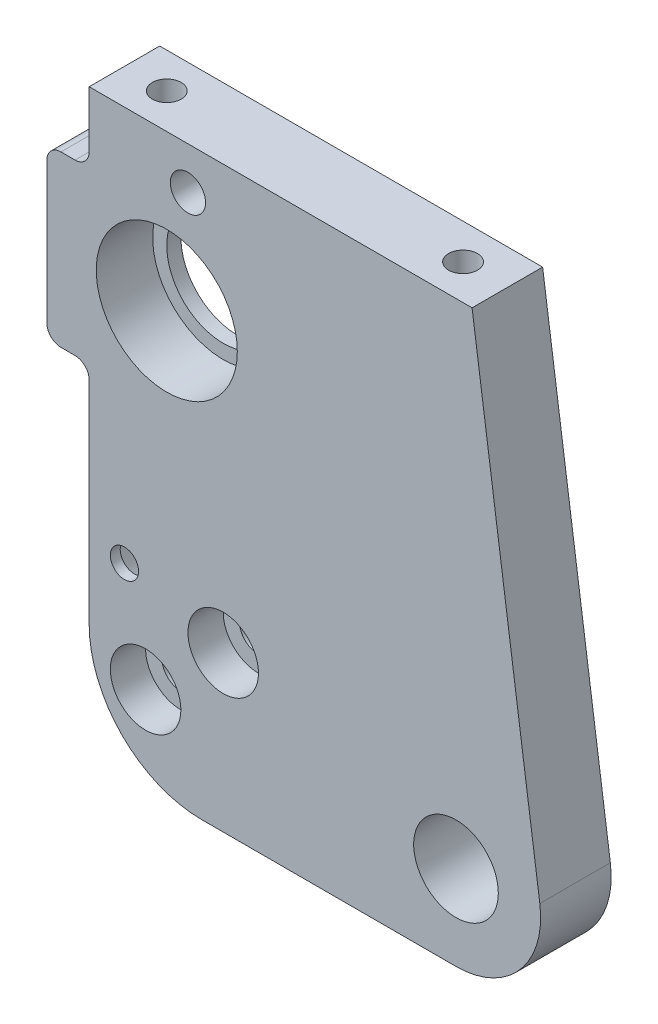
SolidWorks part; units mm, degrees
material "7075-O (SS)"
ref_plane "前视基准面" through (0, 0, 0) normal (0, 0, 1) x (1, 0, 0)
ref_plane "上视基准面" through (0, 0, 0) normal (0, 1, 0) x (1, 0, 0)
ref_plane "右视基准面" through (0, 0, 0) normal (1, 0, 0) x (0, 0, -1)
sketch "草图1" plane through (0, 0, 0) normal (0, 0, 1) x (1, 0, 0)
  line L1 (0, 0) -> (34, 0)
  line L2 (0, 0) -> (0, -41)
  line L3 (0, -41) -> (34, -41)
  line L4 (34, 0) -> (34, -41)
  dimension "D1" = 34
  dimension "D3" = 41
extrude "拉伸1" add sketch "草图1" along normal blind 5
fillet "圆角1" radius 8 1 edges at (0, -41, 2.5)
sketch "草图2" plane through (0, 0, 5) normal (0, 0, 1) x (1, 0, 0)
  line L0 (0, 0) -> (0, -33) construction
  line L2 (8, -41) -> (34, -41) construction
  circle A0 centre (26, -35) radius 3
  dimension "D2" = 6
  dimension "D3" = 6
  dimension "D1" = 26
extrude "拉伸2" cut sketch "草图2" against normal up to surface (5 mm away) up to face at (14.8686, -23.3314, 0)
sketch "草图3" plane through (0, 0, 5) normal (0, 0, 1) x (1, 0, 0)
  line L0 (0, 0) -> (0, -33) construction
  line L1 (0, -41) -> (34, -41) construction
  circle A0 centre (5.5, -11) radius 4
  dimension "D1" = 5.5
  dimension "D2" = 30
  dimension "D3" = 8
extrude "拉伸3" cut sketch "草图3" against normal up to surface (5 mm away) up to face at (29, -35, 0)
sketch "草图4" plane through (0, 0, 5) normal (0, 0, 1) x (1, 0, 0)
  circle A0 centre (5.5, -11) radius 5
  dimension "D1" = 10
extrude "拉伸4" cut sketch "草图4" against normal blind 4
sketch "草图5" plane through (0, 0, 0) normal (0, 1, 0) x (1, 0, 0)
  line L0 (3, -2.5) -> (24, -2.5)
  line L1 (34, 0) -> (0, 0) construction
  line L2 (17, 0) -> (17, -2.5) construction
  line L3 (0, -5) -> (0, 0) construction
  dimension "D1" = 2.5
  dimension "D2" = 21
  dimension "D3" = 3
hole_wizard "M2.5 螺纹孔1" positions "3D草图1" profile "草图6" tap size "M2.5" standard "GB"
sketch3d "3D草图1"
  point P0 (3, 0, 2.5)
  point P3 (24, 0, 2.5)
sketch "草图6" plane through (3, 0, 2.5) normal (1, 0, 0) x (0, 0, 1)
  line L0 (0, 0) -> (0, 7.9659)
  line L1 (0, 7.9659) -> (1.025, 7.35)
  line L2 (1.025, 7.35) -> (1.025, 0)
  line L5 (1.025, 0) -> (0, 0)
  line L10 (0, 7.9659) -> (-1.025, 7.35) construction
  line L11 (0, -6.35) -> (0, 107.95) construction
  dimension "螺纹孔钻头直径" = 2.05
  dimension "螺纹孔钻头深度" = 7.35
  dimension "导头角度" = 118
cosmetic thread "孔螺蚊线1" parameters "D1"=6, "D2"=2.5
cosmetic thread "孔螺蚊线2" parameters "D1"=6, "D2"=2.5
chamfer "倒角1" [suppressed] distance 0.5 angle 45
chamfer "倒角2" [suppressed] distance 0.5 angle 45
sketch "草图7" plane through (0, 0, 0) normal (0, 0, -1) x (-1, 0, 0)
  line L1 (-8, -41) -> (-34, -41) construction
  line L2 (-31.9416, -34.165) -> (-27.14, 0)
  line L3 (-34, 0) -> (0, 0) construction
  line L4 (-26, -41) -> (-34, -41)
  line L5 (-34, -41) -> (-34, 0) construction
  line L6 (-34, -41) -> (-34, 0)
  line L7 (-34, 0) -> (-27.14, 0)
  arc A0 (-31.9416, -34.165) -> (-26, -41) centre (-26, -35) ccw
  circle A1 centre (-26, -35) radius 3 construction
  dimension "D1" = 6
  dimension "D2" = 8
extrude "拉伸5" cut sketch "草图7" against normal up to surface (5 mm away) up to face at (10.5, -11, 5)
sketch "Sketch1" plane through (0, 0, 0) normal (0, 0, -1) x (-1, 0, 0)
  line L0 (-26, -41) -> (-12, -41)
  line L1 (0, 0) -> (0, -33) construction
  line L2 (0, -28.0198) -> (0, -29)
  line L3 (-29.4415, -39.9149) -> (0, -28.0198)
  line L4 (-26, -35) -> (-29.4415, -39.9149) construction
  line L5 (-8, -41) -> (-26, -41) construction
  arc A0 (-31.9416, -34.165) -> (-26, -41) centre (-26, -35) ccw construction
  arc A1 (-29.4415, -39.9149) -> (-26, -41) centre (-26, -35) ccw
  arc A3 (0, -29) -> (-12, -41) centre (-12, -29) cw
  dimension "D1" = 12
  dimension "D2" = 55
  dimension "D3" = 22
  dimension "D4" = 0
extrude "Extrude1" add sketch "Sketch1" against normal up to surface (5 mm away) up to face at (15.497, -25.3626, 5)
sketch "草图8" plane through (0, 0, 0) normal (0, 0, -1) x (-1, 0, 0)
  line L0 (-8, -41) -> (-26, -41) construction
  line L1 (0, 0) -> (0, -33) construction
  circle A0 centre (-2.5, -28) radius 1
  dimension "D3" = 2
  dimension "D1" = 13
  dimension "D2" = 2.5
extrude "拉伸6" cut sketch "草图8" against normal up to surface (5 mm away) up to face at (15.497, -25.3626, 5)
sketch "草图9" plane through (0, 0, 0) normal (0, 0, -1) x (-1, 0, 0)
  line L0 (-0.7612, -30.7586) -> (-4.7079, -32.1951)
  line L1 (-0.1635, -29.4769) -> (-2.626, -22.7111)
  line L2 (-5.9896, -31.5974) -> (-8.4521, -24.8316)
  line L3 (-3.9078, -22.1134) -> (-7.8545, -23.5499)
  line L4 (-2.5, -28) -> (-7.596, -28) construction
  line L5 (-2.5, -28) -> (-2.5, -23.308) construction
  line L6 (-4, -20.9273) -> (-4, -31.0273) construction
  line L7 (0, 0) -> (0, -33) construction
  line L8 (-4, -28) -> (-5.8811, -22.8317) construction
  arc A0 (-0.1635, -29.4769) -> (-0.7612, -30.7586) centre (-1.1032, -29.8189) cw
  arc A1 (-3.9078, -22.1134) -> (-2.626, -22.7111) centre (-3.5657, -23.0531) cw
  arc A2 (-8.4521, -24.8316) -> (-7.8545, -23.5499) centre (-7.5124, -24.4896) cw
  arc A3 (-4.7079, -32.1951) -> (-5.9896, -31.5974) centre (-5.0499, -31.2554) cw
  point P10 (-4, -28)
  point P19 (-2.9681, -21.7714)
  point P22 (-8.7942, -23.892)
  point P25 (-5.6476, -32.5371)
  dimension "D6" = 1
  dimension "D1" = 1.5
  dimension "D2" = 5.5
  dimension "D3" = 9.2
  dimension "D4" = 6.2
  dimension "D5" = 20
extrude "拉伸7" cut sketch "草图9" against normal blind 2.5
sketch "草图10" plane through (0, 0, 2.5) normal (0, 0, -1) x (-1, 0, 0)
  circle A0 centre (-4, -28) radius 3
  dimension "D1" = 6
extrude "拉伸8" cut sketch "草图10" against normal blind 1.8
sketch "草图11" plane through (0, 0, 5) normal (0, 0, -1) x (-1, 0, 0)
  line L0 (-4, -28) -> (-4, -35) construction
  line L1 (-4, -28) -> (-9.5, -28) construction
  line L2 (-4, -30) -> (-9.5, -30)
  dimension "D1" = 7
  dimension "D2" = 5.5
  dimension "D3" = 5.5
  dimension "D4" = 2
hole_wizard "M2.5 Tapped Hole2" [suppressed] positions "3D草图2" profile "草图12" tap size "M2.5" standard "GB"
sketch3d "3D草图2"
  point P0 (9.5, -25.5, 5)
  point P3 (4, -31.5, 5)
sketch "草图12" plane through (9.5, -25.5, 5) normal (1, 0, 0) x (0, -1, 0)
  line L0 (0, 0) -> (0, 6.9659)
  line L1 (0, 6.9659) -> (1.025, 6.35)
  line L2 (1.025, 6.35) -> (1.025, 0)
  line L5 (1.025, 0) -> (0, 0)
  line L10 (0, 6.9659) -> (-1.025, 6.35) construction
  line L11 (0, -6.35) -> (0, 107.95) construction
  dimension "Tap Drill Dia." = 2.05
  dimension "Tap Drill Depth" = 6.35
  dimension "Drill Angle" = 118
cosmetic thread "Hole Thread5" [suppressed] parameters "D1"=5, "D2"=2.5
cosmetic thread "Hole Thread6" [suppressed] parameters "D1"=5, "D2"=2.5
chamfer "倒角3" [suppressed] distance 0.2 angle 45
sketch "草图15" plane through (0, 0, 0) normal (0, 0, -1) x (-1, 0, 0)
  line L1 (0, 0) -> (0, -33) construction
  line L2 (-27.14, 0) -> (0, 0) construction
  circle A0 centre (-16, -28.5) radius 4
  dimension "D1" = 8
  dimension "D3" = 16
  dimension "D2" = 28.5
hole_wizard "CBORE for M2.5 Hexagon socket head cap screws11" positions "3DSketch1" profile "Sketch5" counterbore size "M2.5" standard "GB" end condition through all
sketch3d "3DSketch1"
  point P0 (4, -35, 5)
sketch "Sketch5" plane through (4, -35, 5) normal (1, 0, 0) x (0, -1, 0)
  line L0 (0, 0) -> (0, 5)
  line L1 (0, 5) -> (1.35, 5)
  line L3 (1.35, 5) -> (1.35, 2.5)
  line L4 (1.35, 2.5) -> (2.5, 2.5)
  line L5 (2.5, 2.5) -> (2.5, 0)
  line L7 (2.5, 0) -> (0, 0)
  line L11 (0, -6.35) -> (0, 107.95) construction
  dimension "Thru Hole Dia." = 2.7
  dimension "Thru Hole Depth" = 5
  dimension "C'Bore Dia." = 5
  dimension "C'Bore Depth" = 2.5
hole_wizard "CBORE for M2.5 Hexagon socket head cap screws12" positions "3DSketch2" profile "Sketch6" counterbore size "M2.5" standard "GB" end condition through all
sketch3d "3DSketch2"
  point P0 (9.5, -30, 5)
sketch "Sketch6" plane through (9.5, -30, 5) normal (1, 0, 0) x (0, -1, 0)
  line L0 (0, 0) -> (0, 5)
  line L1 (0, 5) -> (1.35, 5)
  line L3 (1.35, 5) -> (1.35, 2.5)
  line L4 (1.35, 2.5) -> (2.5, 2.5)
  line L5 (2.5, 2.5) -> (2.5, 0)
  line L7 (2.5, 0) -> (0, 0)
  line L11 (0, -6.35) -> (0, 107.95) construction
  dimension "Thru Hole Dia." = 2.7
  dimension "Thru Hole Depth" = 5
  dimension "C'Bore Dia." = 5
  dimension "C'Bore Depth" = 2.5
sketch "草图20" plane through (0, 0, 0) normal (-1, 0, 0) x (0, 0, 1)
  line L0 (5, -17) -> (5, -5)
  line L1 (5, 0) -> (5, -33) construction
  line L2 (5, -5) -> (0, -5)
  line L3 (0, 0) -> (0, -33) construction
  line L4 (0, -5) -> (0, -17)
  line L5 (0, -17) -> (5, -17)
  line L7 (5, 0) -> (0, 0) construction
  dimension "D1" = 5
  dimension "D2" = 12
extrude "凸台-拉伸1" add sketch "草图20" along normal blind 3
fillet "圆角2" radius 1 4 edges at (0, -5, 2.5) (0, -17, 2.5) (-3, -17, 2.5) (-3, -5, 2.5)
sketch "草图21" plane through (0, 0, 0) normal (0, 0, -1) x (-1, 0, 0)
  line L0 (0, 0) -> (0, -41) construction
  line L1 (0, 0) -> (-34, 0) construction
  point P0 (-7, -3)
  dimension "D1" = 7
  dimension "D2" = 3
hole_wizard "M3x0.5 螺纹孔1" positions "3D草图4" profile "草图23" tap size "M3x0.5" standard "ANSI Metric" end condition through all
sketch3d "3D草图4"
  point P0 (7, -3, 0)
sketch "草图23" plane through (7, -3, 0) normal (1, 0, 0) x (0, 1, 0)
  line L0 (0, 0) -> (0, 5)
  line L1 (0, 5) -> (1.25, 5)
  line L2 (1.25, 5) -> (1.25, 0.275)
  line L3 (1.25, 0.275) -> (1.525, 0)
  line L5 (1.525, 0) -> (0, 0)
  line L6 (-1.25, 0.275) -> (-1.525, 0) construction
  line L11 (0, -6.35) -> (0, 107.95) construction
  dimension "通孔螺纹孔钻头直径" = 2.5
  dimension "通孔螺纹孔钻头深度" = 5
  dimension "近端锥形沉头孔直径" = 3.05
  dimension "近端锥形沉头孔角度" = 90
cosmetic thread "孔螺蚊线3" parameters "D2"=3
